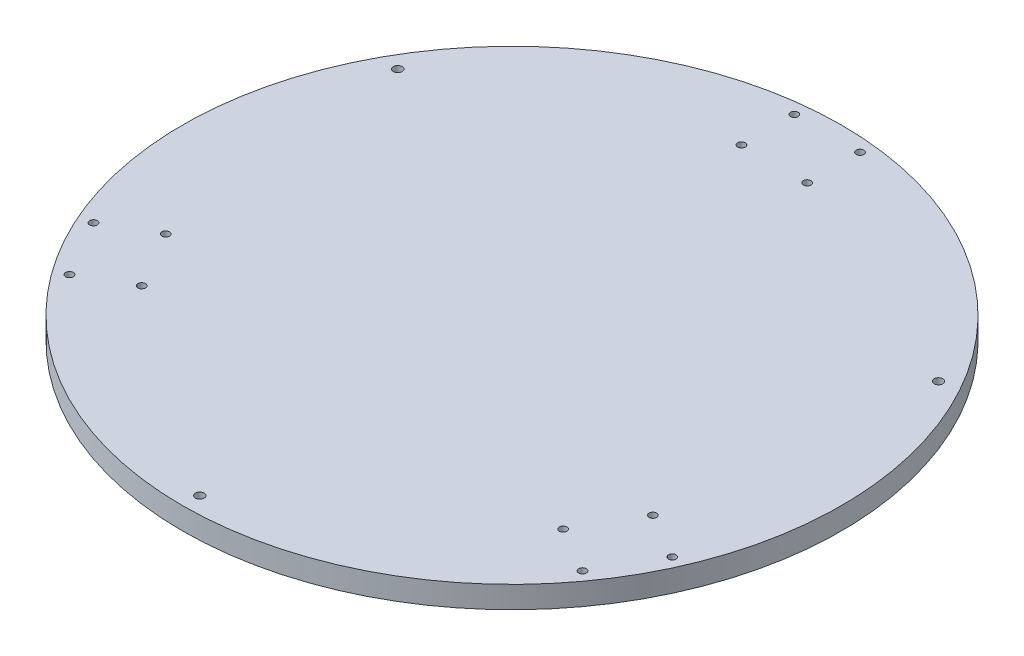
SolidWorks part; units mm, degrees
material "1060 Alloy"
ref_plane "Front Plane" through (0, 0, 0) normal (0, 0, 1) x (1, 0, 0)
ref_plane "Top Plane" through (0, 0, 0) normal (0, 1, 0) x (1, 0, 0)
ref_plane "Right Plane" through (0, 0, 0) normal (1, 0, 0) x (0, 0, -1)
sketch "Sketch1" plane through (0, 0, 0) normal (0, 1, 0) x (1, 0, 0)
  circle A0 centre (0, 0) radius 150
  point P15 (0, 0)
extrude "Boss-Extrude1" add sketch "Sketch1" along normal blind 10
sketch "Sketch2" plane through (0, 10, 0) normal (0, 1, 0) x (1, 0, 0)
  line L0 (0, 0) -> (0, 156.6514) construction
  line L1 (0, 0) -> (135.6641, -78.3257) construction
  line L2 (0, 0) -> (-135.6641, -78.3257) construction
  line L3 (0, 0) -> (0, -155.7893) construction
  line L4 (0, 0) -> (-134.9175, 77.8947) construction
  line L5 (0, 0) -> (134.9175, 77.8947) construction
  circle A0 centre (-14.945, 143.4527) radius 1.73
  circle A1 centre (-14.945, 119.3927) radius 1.73
  circle A2 centre (14.945, 143.4527) radius 1.73
  circle A3 centre (14.945, 119.3927) radius 1.73
  circle A4 centre (95.9246, -72.6391) radius 1.73
  circle A5 centre (116.7612, -84.6691) radius 1.73
  circle A6 centre (131.7062, -58.7836) radius 1.73
  circle A7 centre (110.8696, -46.7536) radius 1.73
  circle A8 centre (-110.8696, -46.7536) radius 1.73
  circle A9 centre (-131.7062, -58.7836) radius 1.73
  circle A10 centre (-116.7612, -84.6691) radius 1.73
  circle A11 centre (-95.9246, -72.6391) radius 1.73
  circle A13 centre (-123.0621, 71.05) radius 2
  circle A14 centre (123.0621, 71.05) radius 2
  circle A15 centre (0, -142.0999) radius 2
  point P8 (0, 0)
  point P33 (0, 0)
  point P37 (0, 0)
  point P44 (0, 0)
  dimension "D2" = 3.46
  dimension "D7" = 4
  dimension "D3" = 14.945
  dimension "D4" = 24.06
  dimension "D1" = 3
  dimension "D5" = 3
  dimension "D6" = 3
  dimension "D8" = 3
extrude "Cut-Extrude1" cut sketch "Sketch2" against normal blind 10
